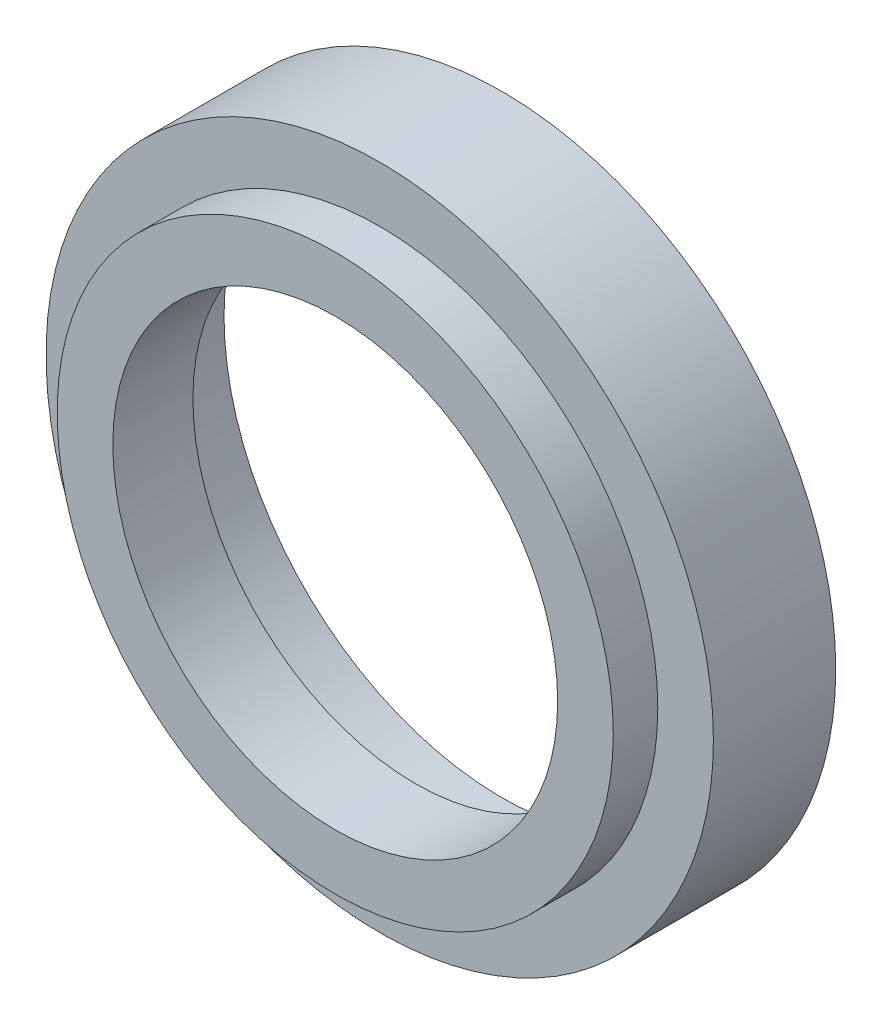
SolidWorks part; units mm, degrees
ref_plane "Plan de face" through (0, 0, 0) normal (0, 0, 1) x (1, 0, 0)
ref_plane "Plan de dessus" through (0, 0, 0) normal (0, 1, 0) x (1, 0, 0)
ref_plane "Plan de droite" through (0, 0, 0) normal (1, 0, 0) x (0, 0, -1)
sketch "Esquisse1" plane through (0, 0, 0) normal (0, 0, 1) x (1, 0, 0)
  circle A0 centre (0, 0) radius 15
extrude "Boss.-Extru.1" add sketch "Esquisse1" along normal blind 7.5
sketch "Esquisse3" plane through (0, 0, 0) normal (0, 0, -1) x (-1, 0, 0)
  circle A0 centre (0, 0) radius 12.5
extrude "Enlèv. mat.-Extru.1" cut sketch "Esquisse3" against normal blind 3.9
sketch "Esquisse4" plane through (0, 0, 7.5) normal (0, 0, 1) x (1, 0, 0)
  circle A0 centre (0, 0) radius 12.5
  circle A1 centre (0, 0) radius 15.5
extrude "Enlèv. mat.-Extru.2" cut sketch "Esquisse4" against normal blind 2
sketch "Esquisse5" plane through (0, 0, 7.5) normal (0, 0, 1) x (1, 0, 0)
  circle A0 centre (0, 0) radius 10
extrude "Enlèv. mat.-Extru.4" cut sketch "Esquisse5" against normal blind 5
